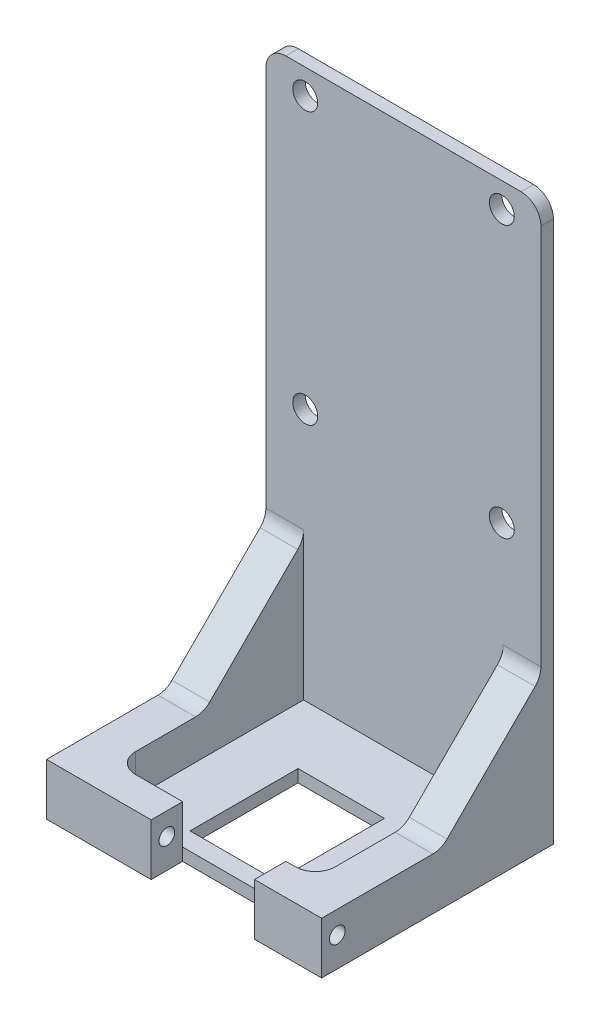
SolidWorks part; units mm, degrees
ref_plane "Front Plane" through (0, 0, 0) normal (0, 0, 1) x (1, 0, 0)
ref_plane "Top Plane" through (0, 0, 0) normal (0, 1, 0) x (1, 0, 0)
ref_plane "Right Plane" through (0, 0, 0) normal (1, 0, 0) x (0, 0, -1)
sketch "Sketch1" plane through (0, 0, 0) normal (0, 1, 0) x (1, 0, 0)
  line L1 (-35, -29.5) -> (35, -29.5)
  line L2 (-35, -29.5) -> (-35, 29.5)
  line L3 (-35, 29.5) -> (35, 29.5)
  line L4 (35, -29.5) -> (35, 29.5)
  line L5 (-35, -29.5) -> (35, 29.5) construction
  line L6 (-35, 29.5) -> (35, -29.5) construction
  point P0 (0, 0)
  dimension "D1" = 70
  dimension "D2" = 59
extrude "Boss-Extrude1" add sketch "Sketch1" along normal blind 3.175
sketch "Sketch2" plane through (0, 3.175, 0) normal (0, 1, 0) x (1, 0, 0)
  line L0 (35, -29.5) -> (35, 29.5) construction
  line L1 (-35, 29.5) -> (35, 29.5)
  line L2 (-35, 29.5) -> (-35, 26.325)
  line L3 (-35, 26.325) -> (35, 26.325)
  line L4 (35, 29.5) -> (35, 26.325)
  dimension "D1" = 3.175
extrude "Boss-Extrude2" add sketch "Sketch2" along normal blind 139.7
sketch "Sketch4" plane through (0, 3.175, 0) normal (0, 1, 0) x (1, 0, 0)
  line L0 (0, 26.325) -> (0, -29.5) construction
  line L5 (-15.882, -21.5) -> (-8.382, -21.5)
  line L6 (-15.882, -21.5) -> (-15.882, -29.5)
  line L7 (-15.882, -29.5) -> (-8.382, -29.5)
  line L8 (-8.382, -21.5) -> (-8.382, -29.5)
  line L9 (-15.882, -21.5) -> (-8.382, -29.5) construction
  line L10 (-15.882, -29.5) -> (-8.382, -21.5) construction
  line L11 (-35, 26.325) -> (35, 26.325) construction
  line L12 (-35, -29.5) -> (35, -29.5) construction
  line L13 (17.907, -21.5) -> (17.907, -29.5)
  line L14 (17.907, -21.5) -> (25.407, -21.5)
  line L15 (25.407, -21.5) -> (25.407, -29.5)
  line L16 (17.907, -29.5) -> (25.407, -29.5)
  point P0 (-12.132, -25.5)
  dimension "D1" = 8.382
  dimension "D2" = 7.5
  dimension "D3" = 8
  dimension "D5" = 26.289
  dimension "D4" = 2
extrude "Boss-Extrude3" add sketch "Sketch4" along normal blind 10
sketch "Sketch5" plane through (0, 3.175, 0) normal (0, 1, 0) x (1, 0, 0)
  line L5 (-8.382, -21.5) -> (17.907, -21.5)
  line L6 (-8.382, -21.5) -> (-8.382, -29.5)
  line L7 (-8.382, -29.5) -> (17.907, -29.5)
  line L8 (17.907, -21.5) -> (17.907, -29.5)
extrude "Cut-Extrude2" cut sketch "Sketch5" against normal blind 10
sketch "Sketch3" plane through (0, 0, -26.325) normal (0, 0, 1) x (1, 0, 0)
  line L0 (-35, 142.875) -> (35, 3.175)
  line L1 (-35, 142.875) -> (35, 142.875) construction
  circle A0 centre (-25, 136.525) radius 3.175
  circle A1 centre (25.038, 136.525) radius 3.175
  circle A2 centre (25.038, 67.437) radius 3.175
  circle A3 centre (-25, 67.437) radius 3.175
  point P6 (0, 73.025)
  dimension "D1" = 25
  dimension "D2" = 6.35
  dimension "D3" = 2
  dimension "D4" = 2
extrude "Cut-Extrude1" cut sketch "Sketch3" against normal blind 139.7 contours A0 | A3 | A2 | A1
sketch "Sketch9" plane through (0, 3.175, 0) normal (0, 1, 0) x (1, 0, 0)
  line L0 (0, 26.325) -> (0, -38.7841) construction
  line L1 (25.407, -29.5) -> (35, -29.5)
  line L2 (25.407, -29.5) -> (25.407, 26.325)
  line L3 (25.407, 26.325) -> (35, 26.325)
  line L4 (35, -29.5) -> (35, 26.325)
  line L9 (-35, 26.325) -> (35, 26.325) construction
  line L10 (-25.407, 26.325) -> (-35, 26.325)
  line L11 (-35, -29.5) -> (-35, 26.325)
  line L12 (-25.407, -29.5) -> (-35, -29.5)
  line L13 (-25.407, -21.5) -> (-25.407, 26.325)
  line L15 (-15.882, -21.5) -> (-25.407, -21.5)
  line L16 (-15.882, -21.5) -> (-15.882, -29.5)
  line L17 (-15.882, -29.5) -> (-25.407, -29.5)
extrude "Boss-Extrude4" add sketch "Sketch9" along normal up to surface (10 mm away) up to face at (-12.132, 13.175, 25.5)
sketch "Sketch7" plane through (0, 3.175, 0) normal (0, 1, 0) x (1, 0, 0)
  line L0 (17.907, -21.5) -> (-8.382, -21.5) construction
  line L1 (-11, -17) -> (11, -17)
  line L2 (-11, -17) -> (-11, 10.5)
  line L3 (-11, 10.5) -> (11, 10.5)
  line L4 (11, -17) -> (11, 10.5)
  line L11 (0, 10.5) -> (0, -17) construction
  dimension "D1" = 4.5
  dimension "D2" = 22
  dimension "D3" = 27.5
extrude "Cut-Extrude6" cut sketch "Sketch7" against normal blind 10
sketch "Sketch12" plane through (-8.382, 0, 0) normal (1, 0, 0) x (0, 0, -1)
  line L0 (-25.5, 13.175) -> (-25.5, 0) construction
  line L1 (-29.5, 13.175) -> (-21.5, 13.175) construction
  line L2 (-29.5, 0) -> (-21.5, 0) construction
  circle A0 centre (-25.5, 7.475) radius 2
  dimension "D1" = 4.3
extrude "Cut-Extrude7" cut sketch "Sketch12" against normal through all both and the other way through all
sketch "Sketch13" plane through (-35, 0, 0) normal (-1, 0, 0) x (0, 0, 1)
  line L0 (-26.325, 13.175) -> (-26.325, 38.575)
  line L1 (-26.325, 142.875) -> (-26.325, 13.175) construction
  line L2 (-26.325, 38.575) -> (-0.925, 13.175)
  line L3 (-26.325, 13.175) -> (29.5, 13.175) construction
  line L4 (-0.925, 13.175) -> (-26.325, 13.175)
  dimension "D1" = 25.4
  dimension "D2" = 25.4
extrude "Boss-Extrude5" add sketch "Sketch13" against normal up to surface (9.593 mm away) up to face at (-25.407, 8.175, -2.4125)
sketch "Sketch14" plane through (35, 0, 0) normal (1, 0, 0) x (0, 0, -1)
  line L0 (26.325, 13.175) -> (26.325, 38.575)
  line L1 (26.325, 142.875) -> (26.325, 13.175) construction
  line L2 (26.325, 38.575) -> (0.925, 13.175)
  line L3 (-29.5, 13.175) -> (26.325, 13.175) construction
  line L4 (0.925, 13.175) -> (26.325, 13.175)
  dimension "D1" = 25.4
  dimension "D2" = 25.4
extrude "Boss-Extrude6" add sketch "Sketch14" against normal up to surface (9.593 mm away) up to face at (25.407, 8.175, -2.4125)
fillet "Fillet1" radius 5.08 2 edges at (35, 142.875, -27.9125) (-35, 142.875, -27.9125)
fillet "Fillet2" radius 5.08 4 edges at (-30.2035, 38.575, -26.325) (-30.2035, 13.175, -0.925) (30.2035, 13.175, -0.925) (30.2035, 38.575, -26.325)
fillet "Fillet3" radius 5.08 2 edges at (25.407, 8.175, 21.5) (-25.407, 8.175, 21.5)
